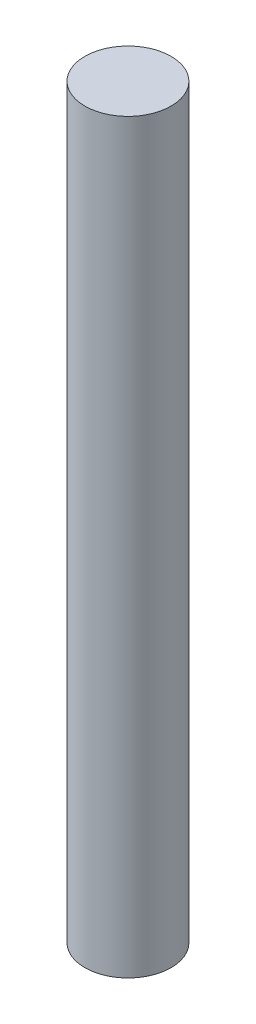
SolidWorks part; units mm, degrees
ref_plane "Front Plane" through (0, 0, 0) normal (0, 0, 1) x (1, 0, 0)
ref_plane "Top Plane" through (0, 0, 0) normal (0, 1, 0) x (1, 0, 0)
ref_plane "Right Plane" through (0, 0, 0) normal (1, 0, 0) x (0, 0, -1)
sketch "Sketch1" plane through (0, 0, 0) normal (0, 1, 0) x (1, 0, 0)
  circle A0 centre (0, 0) radius 1.45
  dimension "D1" = 2.9
extrude "Boss-Extrude1" add sketch "Sketch1" along normal blind 25.1
